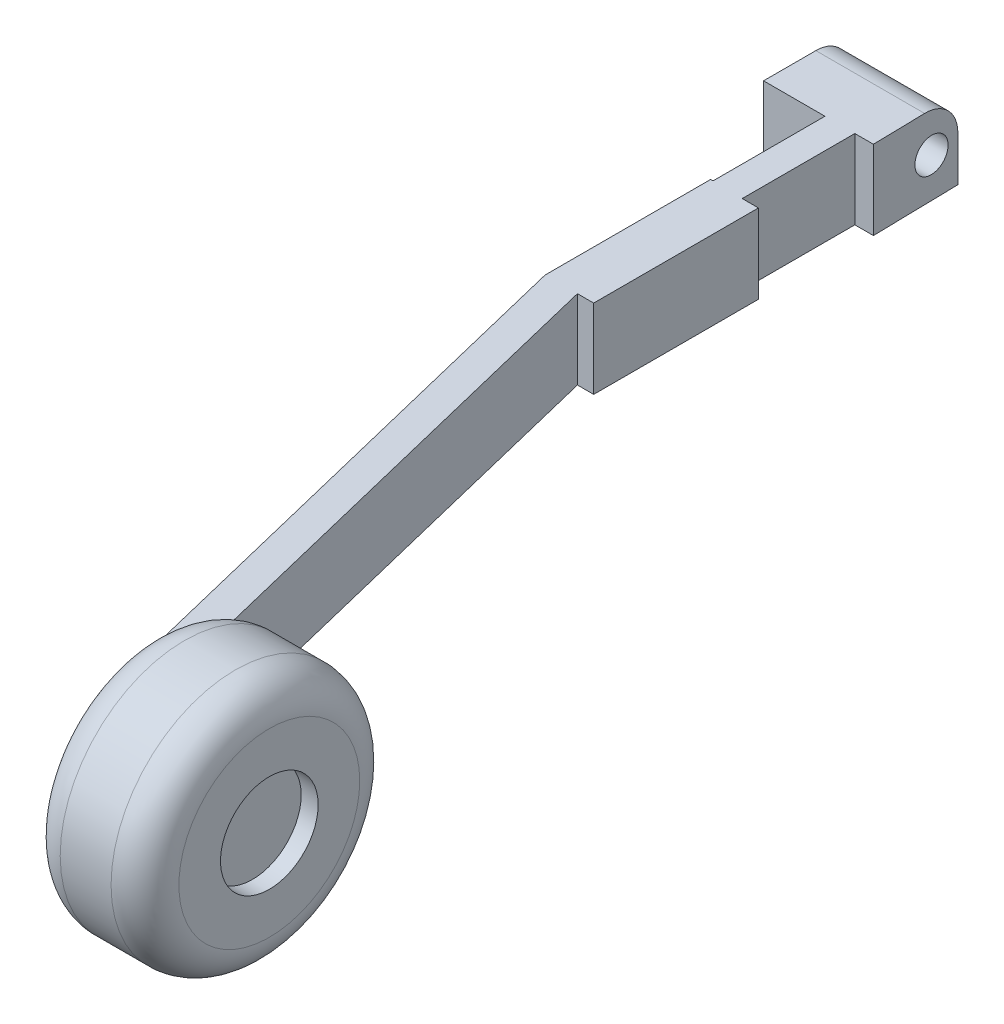
SolidWorks part; units mm, degrees
ref_plane "Front Plane" through (0, 0, 0) normal (0, 0, 1) x (1, 0, 0)
ref_plane "Top Plane" through (0, 0, 0) normal (0, 1, 0) x (1, 0, 0)
ref_plane "Right Plane" through (0, 0, 0) normal (1, 0, 0) x (0, 0, -1)
sketch "Sketch1" plane through (0, 0, 0) normal (0, 1, 0) x (1, 0, 0)
  line L0 (0, 0) -> (0, 88) construction
  line L2 (-14.7557, 80.3744) -> (-9.3252, 80.3744)
  line L3 (-5.1961, 88) -> (-14.7557, 88)
  line L4 (-14.7557, 88) -> (-14.7557, 80.3744)
  line L5 (-9.3252, 80.3744) -> (-9.3252, 70.4742)
  line L7 (-5.1961, 88) -> (-5.0369, 80.3744)
  line L9 (-9.3252, 70.4742) -> (-9.5394, 70.4742)
  line L10 (-9.5394, 70.4742) -> (-9.5394, 55.8322)
  line L13 (-5.0369, 80.3744) -> (-6.68, 80.3744)
  line L14 (-6.68, 80.3744) -> (-6.68, 72.0145)
  line L15 (-6.68, 72.0145) -> (-6.68, 70.4073)
  line L16 (-6.68, 70.4073) -> (-5.2418, 70.4073)
  line L17 (-5.2418, 70.4073) -> (-5.2418, 55.8322)
  line L28 (-9.5394, 55.8322) -> (3.5253, 2.2747)
  line L29 (3.5253, 2.2747) -> (5.5091, 2.2747)
  line L30 (5.5091, 2.2747) -> (5.5091, 5.8833)
  line L31 (5.5091, 5.8833) -> (-6.68, 55.8322)
  line L32 (-6.68, 55.8322) -> (-5.2418, 55.8322)
  dimension "D1" = 88
extrude "Boss-Extrude1" add sketch "Sketch1" along normal mid plane 7
sketch "Sketch2" plane through (-14.7557, 0, 0) normal (-1, 0, 0) x (0, 0, 1)
  circle A0 centre (-85.6215, 0) radius 1.5
  dimension "D1" = 3
extrude "Cut-Extrude1" cut sketch "Sketch2" against normal blind 27
sketch "Sketch8" plane through (5.5091, 0, 0) normal (1, 0, 0) x (0, 0, -1)
  circle A1 centre (4.3848, 0) radius 1.5
  dimension "D1" = 3
extrude "Boss-Extrude6" add sketch "Sketch8" along normal blind 1.5
sketch "Sketch9" plane through (7.0091, 0, 0) normal (1, 0, 0) x (0, 0, -1)
  circle A1 centre (4.3848, 0) radius 11
  dimension "D1" = 22
extrude "Boss-Extrude7" add sketch "Sketch9" along normal blind 10.5
fillet "Fillet11" radius 3 1 edges at (-9.9759, 3.5, -88)
fillet "Fillet12" radius 3 2 edges at (7.0091, 0, -15.3848) (17.5091, 0, -15.3848)
sketch "Sketch12" plane through (17.5091, 0, 0) normal (1, 0, 0) x (0, 0, -1)
  circle A0 centre (4.3848, 0) radius 4.3187
extrude "Cut-Extrude2" cut sketch "Sketch12" against normal blind 1.5
